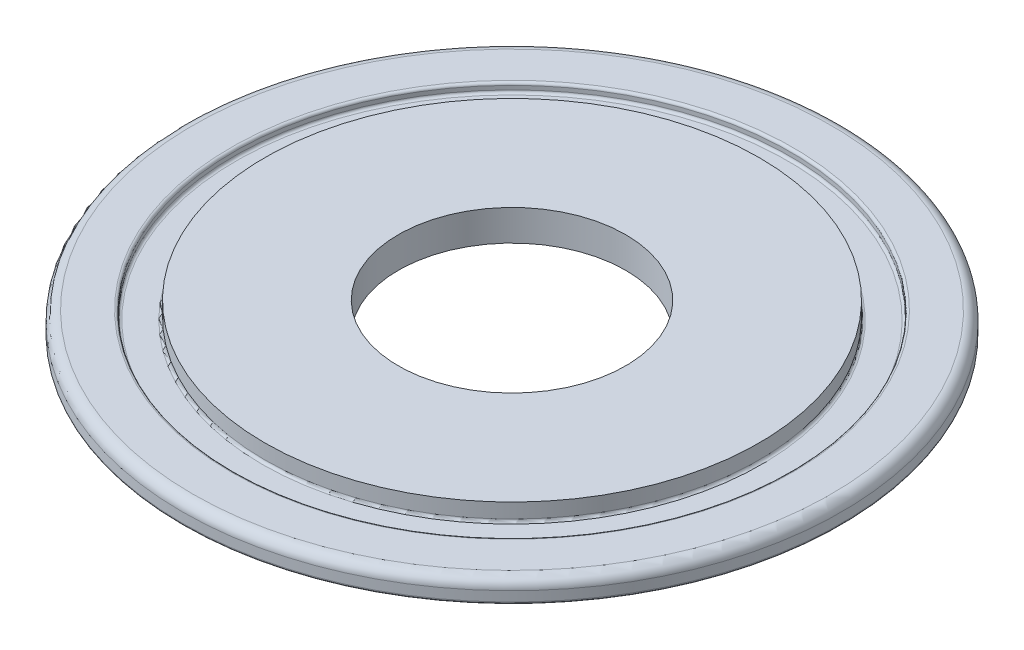
SolidWorks part; units mm, degrees
material "HDPE "
ref_plane "Front Plane" through (0, 0, 0) normal (0, 0, 1) x (1, 0, 0)
ref_plane "Top Plane" through (0, 0, 0) normal (0, 1, 0) x (1, 0, 0)
ref_plane "Right Plane" through (0, 0, 0) normal (1, 0, 0) x (0, 0, -1)
sketch "Sketch1" plane through (0, 0, 0) normal (0, 0, 1) x (1, 0, 0)
  line L0 (0, 0) -> (0, 15.5783) construction
  line L1 (17.526, 0) -> (17.526, 2.0955)
  line L2 (17.526, 2.0955) -> (22.098, 2.0955) construction
  line L3 (22.098, 2.0955) -> (22.098, 3.4925) construction
  line L4 (22.098, 3.4925) -> (50.8, 3.4925) construction
  line L5 (50.8, 3.4925) -> (50.8, 0)
  line L6 (50.8, 0) -> (17.526, 0)
  line L7 (22.5211, 4.7625) -> (16.0975, 4.7625) construction
  line L8 (50.8, 6.0325) -> (42.926, 6.0325) construction
  line L9 (42.926, 6.0325) -> (42.926, 7.4295) construction
  line L10 (17.7748, 4.7625) -> (38.1, 4.7625) construction
  line L11 (17.7748, 4.7625) -> (17.7748, 9.525) construction
  line L12 (17.7748, 9.525) -> (50.8, 9.525) construction
  line L13 (50.8, 9.525) -> (50.8, 6.0325) construction
  line L14 (38.1, 4.7625) -> (38.1, 7.4295) construction
  line L15 (38.1, 7.4295) -> (42.926, 7.4295) construction
  line L16 (50.8, 3.4925) -> (42.926, 3.4925)
  line L17 (42.926, 3.4925) -> (42.926, 2.0955)
  line L18 (42.926, 2.0955) -> (38.1, 2.0955)
  line L19 (38.1, 2.0955) -> (38.1, 4.7625)
  line L20 (38.1, 4.7625) -> (17.526, 4.7625)
  line L21 (17.526, 4.7625) -> (17.526, 2.0955)
  dimension "D1" = 2.667
  dimension "D2" = 1.27
  dimension "D3" = 9.525
  dimension "D4" = 35.052
  dimension "D5" = 101.6
  dimension "D6" = 4.572
  dimension "D7" = 2.54
  dimension "D8" = 4.826
  dimension "D9" = 76.2
  dimension "D10" = 2.0955
revolve "Revolve1" add sketch "Sketch1" angle 360 about L0
sketch "Sketch2" plane through (0, 0, 0) normal (0, -1, 0) x (1, 0, 0)
  circle A0 centre (0, 0) radius 19.3929
  dimension "D1" = 38.7858
extrude "FEACut-Extrude1" [suppressed] cut sketch "Sketch2" against normal blind 0.0254
fillet "Fillet1" radius 0.3969 4 edges at (0, 0, -50.8) (0, 3.4925, -42.926) (0, 2.0955, -38.1) (0, 2.0955, -42.926)
fillet "Fillet2" radius 1.5875 1 edges at (0, 3.4925, -50.8)
